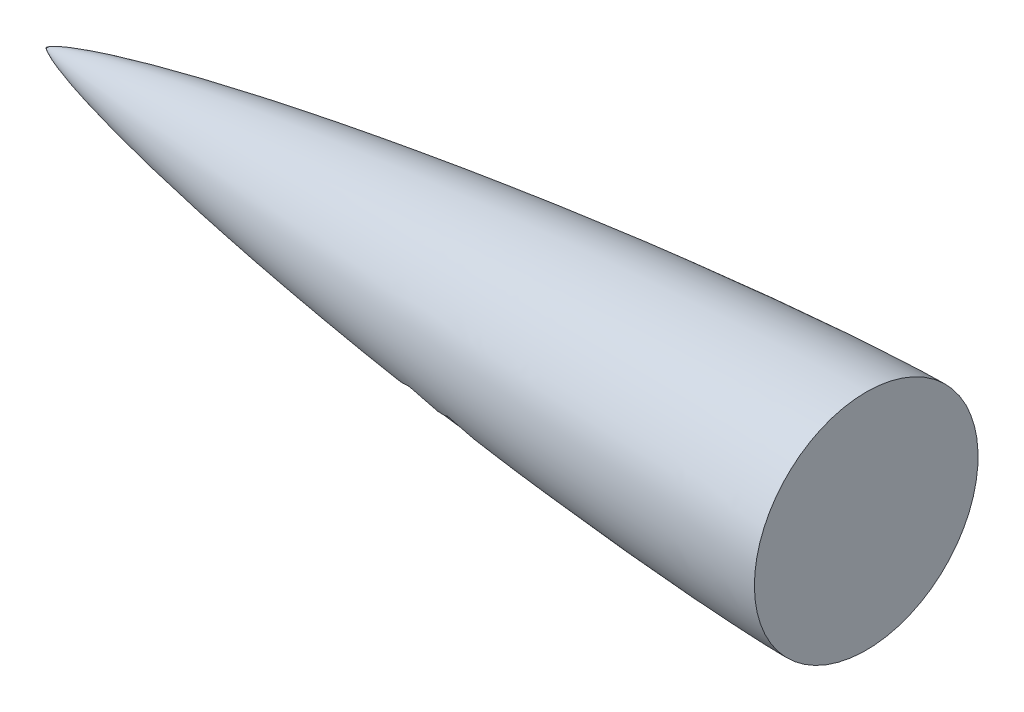
SolidWorks part; units mm, degrees
ref_plane "Front Plane" through (0, 0, 0) normal (0, 0, 1) x (1, 0, 0)
ref_plane "Top Plane" through (0, 0, 0) normal (0, 1, 0) x (1, 0, 0)
ref_plane "Right Plane" through (0, 0, 0) normal (1, 0, 0) x (0, 0, -1)
sketch "Sketch9" plane through (0, 0, 0) normal (0, 0, 1) x (1, 0, 0)
  line L0 (0, 0) -> (22, 0)
  line L1 (22, 0) -> (22, 3)
  spline S0 degree 4 poles (0, 0) (0.0018, 0.0034) (0.0061, 0.0091) (0.0142, 0.016) (0.0261, 0.0253) (0.0414, 0.0356) (0.0649, 0.0498) (0.1045, 0.0713) (0.1739, 0.1046) (0.2996, 0.1573) (0.5263, 0.2398) (0.9018, 0.3579) (1.5784, 0.5427) (2.5342, 0.7661) (3.7204, 1.0098) (5.082, 1.2591) (6.4498, 1.4869) (7.8205, 1.6966) (9.1935, 1.8907) (10.5684, 2.0705) (11.945, 2.2369) (13.3231, 2.3904) (14.7026, 2.531) (16.0834, 2.6582) (17.4654, 2.7714) (18.8486, 2.8688) (20.1551, 2.9436) (21.1163, 2.9828) (21.7314, 2.9983) (22, 3) knots 0 0 0 0 0 0.000696 0.001285 0.001879 0.002733 0.003996 0.006219 0.009974 0.016536 0.028475 0.049524 0.080651 0.142462 0.204716 0.266969 0.329223 0.391477 0.453731 0.515984 0.578238 0.640492 0.702745 0.764999 0.827253 0.889506 0.95176 1 1 1 1 1 construction
  spline S1 degree 4 poles (0, 0) (0.0018, 0.0034) (0.0061, 0.0091) (0.0142, 0.016) (0.0261, 0.0253) (0.0414, 0.0356) (0.0649, 0.0498) (0.1045, 0.0713) (0.1739, 0.1046) (0.2996, 0.1573) (0.5263, 0.2398) (0.9018, 0.3579) (1.5784, 0.5427) (2.5342, 0.7661) (3.7204, 1.0098) (5.082, 1.2591) (6.4498, 1.4869) (7.8205, 1.6966) (9.1935, 1.8907) (10.5684, 2.0705) (11.945, 2.2369) (13.3231, 2.3904) (14.7026, 2.531) (16.0834, 2.6582) (17.4654, 2.7714) (18.8486, 2.8688) (20.1551, 2.9436) (21.1163, 2.9828) (21.7314, 2.9983) (22, 3) knots 0 0 0 0 0 0.000696 0.001285 0.001879 0.002733 0.003996 0.006219 0.009974 0.016536 0.028475 0.049524 0.080651 0.142462 0.204716 0.266969 0.329223 0.391477 0.453731 0.515984 0.578238 0.640492 0.702745 0.764999 0.827253 0.889506 0.95176 1 1 1 1 1
  dimension "D1" = 22
revolve "Revolve9" add sketch "Sketch9" angle 360 about L0
